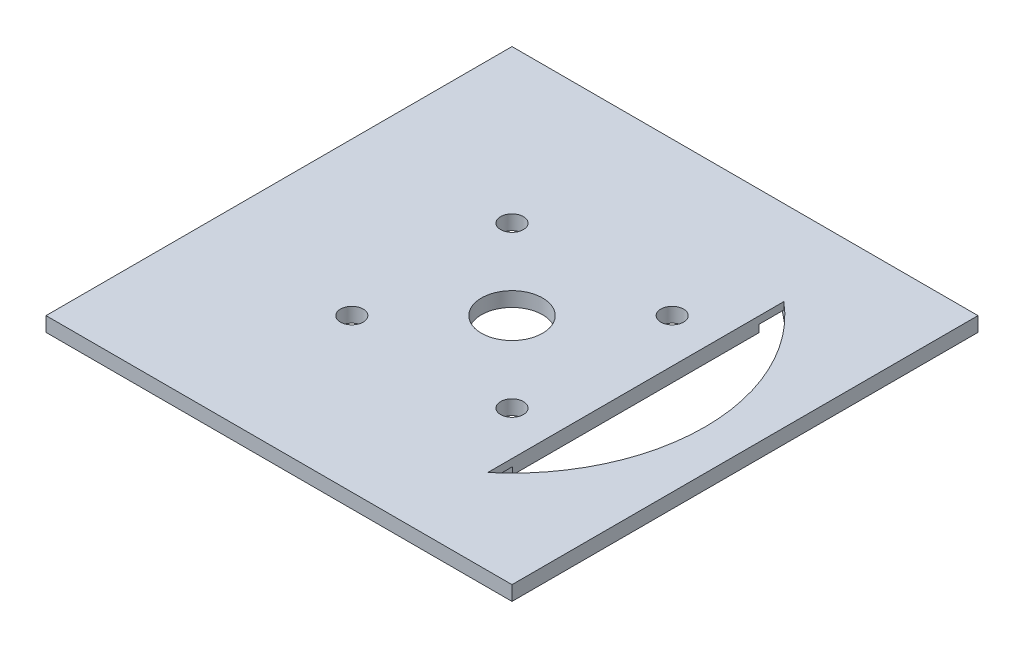
SolidWorks part; units mm, degrees
ref_plane "Front Plane" through (0, 0, 0) normal (0, 0, 1) x (1, 0, 0)
ref_plane "Top Plane" through (0, 0, 0) normal (0, 1, 0) x (1, 0, 0)
ref_plane "Right Plane" through (0, 0, 0) normal (1, 0, 0) x (0, 0, -1)
sketch "Sketch1" plane through (0, 0, 0) normal (0, 1, 0) x (1, 0, 0)
  line L0 (-146.8014, 0) -> (146.8014, 0) construction
  line L1 (0, -118.2881) -> (0, 118.2881) construction
  line L3 (-101.6, -101.6) -> (101.6, -101.6)
  line L4 (-101.6, -101.6) -> (-101.6, 101.6)
  line L5 (-101.6, 101.6) -> (101.6, 101.6)
  line L6 (101.6, -101.6) -> (101.6, 101.6)
  line L7 (-101.6, -101.6) -> (101.6, 101.6) construction
  line L8 (-101.6, 101.6) -> (101.6, -101.6) construction
  circle A0 centre (0, 0) radius 76.2 construction
  circle A1 centre (0, 0) radius 84.1375 construction
  point P4 (0, 0)
  point P8 (0, 0)
  dimension "D1" = 152.4
  dimension "D2" = 168.275
  dimension "D3" = 203.2
  dimension "D4" = 203.2
extrude "Boss-Extrude1" add sketch "Sketch1" along normal mid plane 6.35
sketch "Sketch2" plane through (0, 0, 0) normal (0, 1, 0) x (1, 0, 0)
  line L0 (-170.4219, 0) -> (170.4219, 0) construction
  line L1 (0, -147.4508) -> (0, 147.4508) construction
  line L2 (53.975, -64.5432) -> (53.975, 64.5432)
  line L3 (-34.925, -47.625) -> (34.925, -47.625) construction
  line L4 (-47.625, -34.925) -> (-47.625, 34.925) construction
  line L5 (-34.925, 47.625) -> (34.925, 47.625) construction
  line L6 (47.625, -34.925) -> (47.625, 34.925) construction
  line L7 (-47.625, -47.625) -> (47.625, 47.625) construction
  line L8 (-47.625, 47.625) -> (47.625, -47.625) construction
  circle A0 centre (0, 0) radius 76.2 construction
  circle A1 centre (0, 0) radius 84.1375 construction
  arc A2 (-34.925, -47.625) -> (-47.625, -34.925) centre (-34.925, -34.925) cw construction
  arc A3 (34.925, -47.625) -> (47.625, -34.925) centre (34.925, -34.925) ccw construction
  arc A4 (34.925, 47.625) -> (47.625, 34.925) centre (34.925, 34.925) cw construction
  arc A5 (-47.625, 34.925) -> (-34.925, 47.625) centre (-34.925, 34.925) cw construction
  arc A6 (53.975, -64.5432) -> (53.975, 64.5432) centre (0, 0) ccw
  point P4 (0, 0)
  point P8 (0, 0)
  point P30 (53.975, 0)
  dimension "D1" = 152.4
  dimension "D2" = 168.275
  dimension "D5" = 12.7
  dimension "D3" = 95.25
  dimension "D4" = 95.25
  dimension "D6" = 6.35
extrude "Cut-Extrude1" cut sketch "Sketch2" against normal mid plane 12.7
sketch "Sketch3" plane through (0, 3.175, 0) normal (0, 1, 0) x (1, 0, 0)
  line L0 (-147.1684, 0) -> (147.1684, 0) construction
  line L1 (0, -109.8086) -> (0, 109.8086) construction
  line L3 (-34.925, -47.625) -> (34.925, -47.625) construction
  line L4 (-47.625, -34.925) -> (-47.625, 34.925) construction
  line L5 (-34.925, 47.625) -> (34.925, 47.625) construction
  line L6 (47.625, -34.925) -> (47.625, 34.925) construction
  line L7 (-47.625, -47.625) -> (47.625, 47.625) construction
  line L8 (-47.625, 47.625) -> (47.625, -47.625) construction
  arc A0 (-34.925, -47.625) -> (-47.625, -34.925) centre (-34.925, -34.925) cw construction
  arc A1 (34.925, -47.625) -> (47.625, -34.925) centre (34.925, -34.925) ccw construction
  arc A2 (34.925, 47.625) -> (47.625, 34.925) centre (34.925, 34.925) cw construction
  arc A3 (-47.625, 34.925) -> (-34.925, 47.625) centre (-34.925, 34.925) cw construction
  circle A4 centre (-34.925, -34.925) radius 4.953
  circle A6 centre (-34.925, 34.925) radius 4.953
  circle A7 centre (34.925, 34.925) radius 4.953
  circle A8 centre (34.925, -34.925) radius 4.953
  circle A9 centre (0, 0) radius 13.335
  point P0 (0, 0)
  point P4 (0, 0)
  point P8 (0, 0)
  dimension "D3" = 12.7
  dimension "D4" = 9.906
  dimension "D7" = 9.906
  dimension "D10" = 9.906
  dimension "D11" = 9.906
  dimension "D16" = 26.67
  dimension "D1" = 95.25
  dimension "D2" = 95.25
  dimension "D5" = 12.7
  dimension "D6" = 12.7
  dimension "D8" = 12.7
  dimension "D9" = 12.7
  dimension "D12" = 12.7
  dimension "D13" = 12.7
  dimension "D14" = 12.7
  dimension "D15" = 12.7
extrude "Cut-Extrude2" cut sketch "Sketch3" against normal blind 12.7
sketch "Sketch4" plane through (0, -3.175, 0) normal (0, -1, 0) x (1, 0, 0)
  line L0 (-162.3433, 0) -> (162.3433, 0) construction
  line L1 (0, -118.9405) -> (0, 118.9405) construction
  circle A0 centre (0, 0) radius 76.2
  circle A1 centre (0, 0) radius 84.1375
  point P4 (0, 0)
  point P8 (0, 0)
  dimension "D1" = 152.4
  dimension "D2" = 168.275
extrude "Cut-Extrude3" cut sketch "Sketch4" against normal blind 3.175
